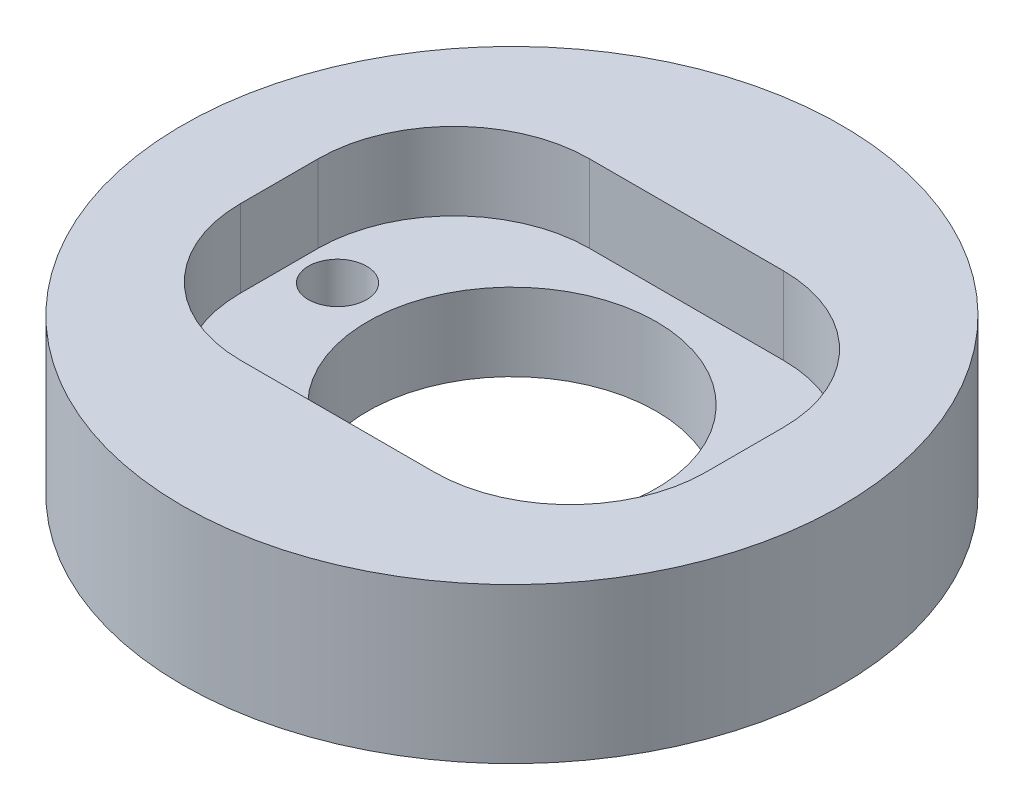
SolidWorks part; units mm, degrees
ref_plane "Front Plane" through (0, 0, 0) normal (0, 0, 1) x (1, 0, 0)
ref_plane "Top Plane" through (0, 0, 0) normal (0, 1, 0) x (1, 0, 0)
ref_plane "Right Plane" through (0, 0, 0) normal (1, 0, 0) x (0, 0, -1)
sketch "Sketch2" plane through (0, 0, 0) normal (0, 1, 0) x (1, 0, 0)
  line L0 (0, 8.5) -> (0, -22.3339) construction
  line L1 (8.5, 0) -> (-25.2541, 0) construction
  circle A0 centre (0, 0) radius 8.5
  dimension "D1" = 17
extrude "Boss-Extrude1" add sketch "Sketch2" along normal blind 4
sketch "Sketch3" plane through (0, 4, 0) normal (0, 1, 0) x (1, 0, 0)
  line L1 (-6, 4.5) -> (6, 4.5)
  line L2 (-6, 4.5) -> (-6, -4.5)
  line L3 (-6, -4.5) -> (6, -4.5)
  line L4 (6, 4.5) -> (6, -4.5)
  line L5 (-6, 4.5) -> (6, -4.5) construction
  line L6 (-6, -4.5) -> (6, 4.5) construction
  point P0 (0, 0)
  dimension "D1" = 12
  dimension "D2" = 9
extrude "Cut-Extrude1" cut sketch "Sketch3" against normal blind 2
fillet "Fillet1" radius 3.5 4 edges at (-6, 3, 4.5) (6, 3, 4.5) (-6, 3, -4.5) (6, 3, -4.5)
sketch "Sketch4" plane through (0, 2, 0) normal (0, 1, 0) x (1, 0, 0)
  line L1 (2.5, 4.5) -> (-2.5, 4.5) construction
  line L2 (0, 0) -> (0, -17.7909) construction
  circle A0 centre (0, 0) radius 3.725
  circle A2 centre (-4.977, 0.4786) radius 0.75
  circle A3 centre (4.977, 0.4786) radius 0.75
  dimension "D1" = 7.45
  dimension "D2" = 5
  dimension "D3" = 4.5
extrude "Cut-Extrude2" cut sketch "Sketch4" against normal through all
ref_plane "Plane1" through (0, 4, 0) normal (0, 1, 0) x (1, 0, 0)
sketch "Sketch5" plane through (0, 4, 0) normal (0, 1, 0) x (1, 0, 0)
  line L0 (0, 0) -> (0, 13.0768) construction
  line L1 (0, 0) -> (17.6113, 0) construction
